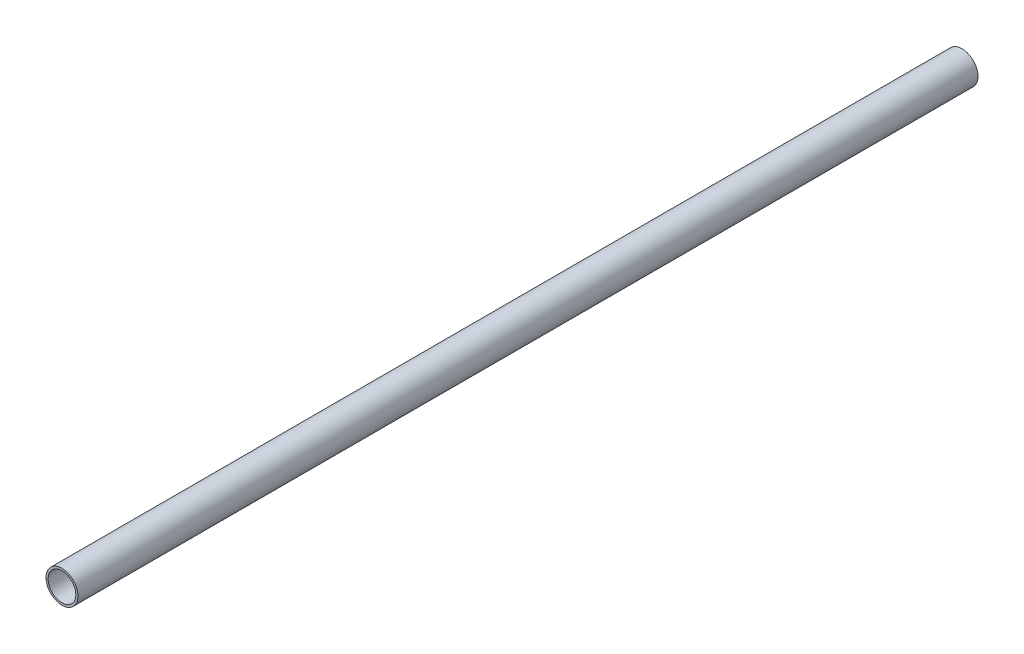
SolidWorks part; units mm, degrees
material "Thornel Mat VMA"
ref_plane "前视基准面" through (0, 0, 0) normal (0, 0, 1) x (1, 0, 0)
ref_plane "上视基准面" through (0, 0, 0) normal (0, 1, 0) x (1, 0, 0)
ref_plane "右视基准面" through (0, 0, 0) normal (1, 0, 0) x (0, 0, -1)
sketch "草图1" plane through (0, 0, 0) normal (0, 0, 1) x (1, 0, 0)
  circle A0 centre (0, 0) radius 6.5
  circle A1 centre (0, 0) radius 7.5
  dimension "D1" = 13
  dimension "D2" = 15
extrude "凸台-拉伸1" add sketch "草图1" along normal blind 422
